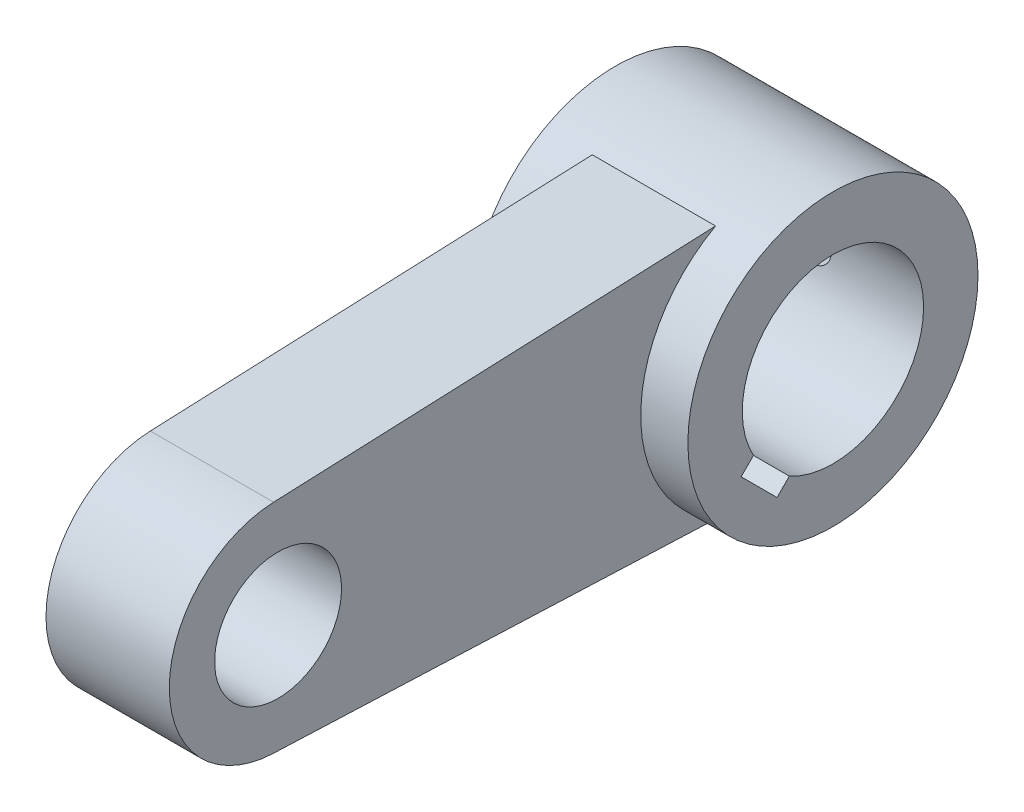
SolidWorks part; units mm, degrees
material "ASTM A36 Steel"
ref_plane "Front Plane" through (0, 0, 0) normal (0, 0, 1) x (1, 0, 0)
ref_plane "Top Plane" through (0, 0, 0) normal (0, 1, 0) x (1, 0, 0)
ref_plane "Right Plane" through (0, 0, 0) normal (1, 0, 0) x (0, 0, -1)
sketch "Sketch1" plane through (0, 0, 0) normal (1, 0, 0) x (0, 0, -1)
  circle A0 centre (0, 0) radius 25
  circle A1 centre (0, 0) radius 40
  dimension "D1" = 50
  dimension "D2" = 80
extrude "Boss-Extrude1" add sketch "Sketch1" along normal mid plane 60
sketch "Sketch2" plane through (0, 0, 0) normal (1, 0, 0) x (0, 0, -1)
  line L0 (-19.3649, 35) -> (-141.236, 29.9745)
  line L1 (-141.236, -29.9745) -> (-19.3649, -35)
  circle A0 centre (0, 0) radius 40 construction
  arc A1 (-141.236, 29.9745) -> (-141.236, -29.9745) centre (-140, 0) ccw
  circle A3 centre (0, 0) radius 40
  arc A4 (-19.3649, 35) -> (-19.3649, -35) centre (0, 0) ccw
  dimension "D2" = 30
  dimension "D1" = 140
  dimension "D3" = 70
  dimension "D4" = 0
extrude "Boss-Extrude2" add sketch "Sketch2" along normal mid plane 34
sketch "Sketch3" plane through (17, 0, 0) normal (1, 0, 0) x (0, 0, -1)
  circle A0 centre (-140, 0) radius 17.5
  dimension "D1" = 35
extrude "Cut-Extrude1" cut sketch "Sketch3" against normal through all
sketch "Sketch5" plane through (30, 0, 0) normal (1, 0, 0) x (0, 0, -1)
  line L0 (-3.7029, 6.1966) -> (-25.3144, -15.4149)
  line L1 (-3.7029, 6.1966) -> (6.1966, -3.7029)
  line L2 (-25.3144, -15.4149) -> (-15.4149, -25.3144)
  line L3 (6.1966, -3.7029) -> (-15.4149, -25.3144)
  line L4 (-20.3647, -20.3647) -> (1.2469, 1.2469) construction
  line L5 (-117.6, 0) -> (0, 0) construction
  dimension "D1" = 28.8
  dimension "D2" = 14
  dimension "D3" = 45
extrude "Cut-Extrude2" cut sketch "Sketch5" against normal through all
ref_plane "Plane1" through (0, 0, -35) normal (0, 0, 1) x (1, 0, 0)
sketch "Sketch6" plane through (0, 0, -35) normal (0, 0, 1) x (1, 0, 0)
  circle A0 centre (0, 0) radius 4.5
  dimension "D1" = 9
extrude "Cut-Extrude3" cut sketch "Sketch6" along normal blind 24
